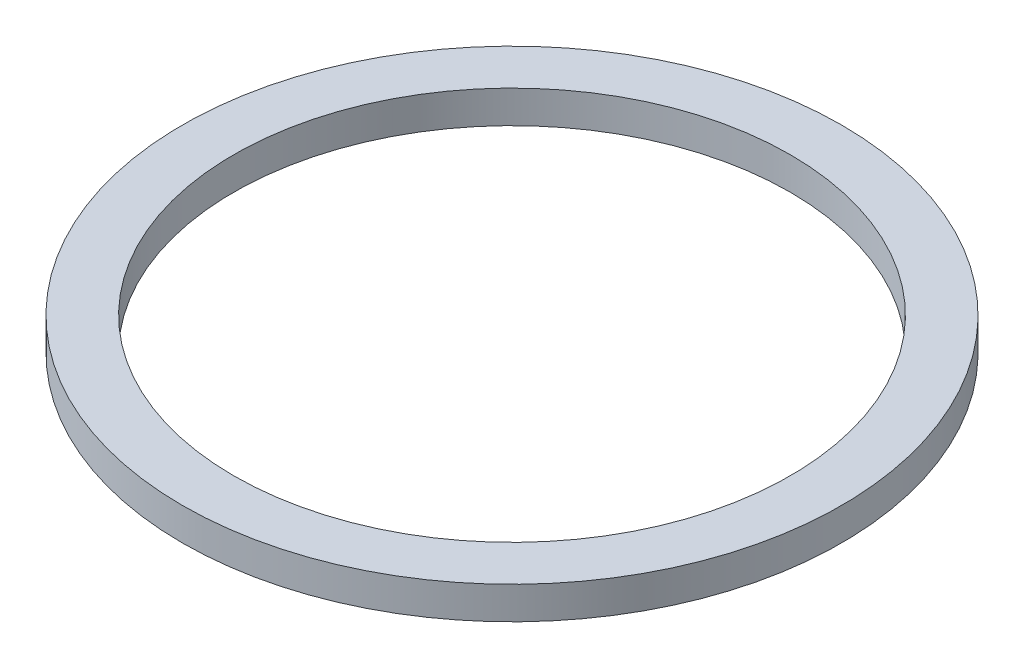
SolidWorks part; units mm, degrees
material "Pine"
ref_plane "Front Plane" through (0, 0, 0) normal (0, 0, 1) x (1, 0, 0)
ref_plane "Top Plane" through (0, 0, 0) normal (0, 1, 0) x (1, 0, 0)
ref_plane "Right Plane" through (0, 0, 0) normal (1, 0, 0) x (0, 0, -1)
sketch "Sketch1" plane through (0, 0, 0) normal (0, 1, 0) x (1, 0, 0)
  circle A0 centre (0, 0) radius 192.5
  circle A1 centre (0, 0) radius 162.5
  dimension "D1" = 385
  dimension "D2" = 325
extrude "Boss-Extrude1" add sketch "Sketch1" along normal mid plane 19
